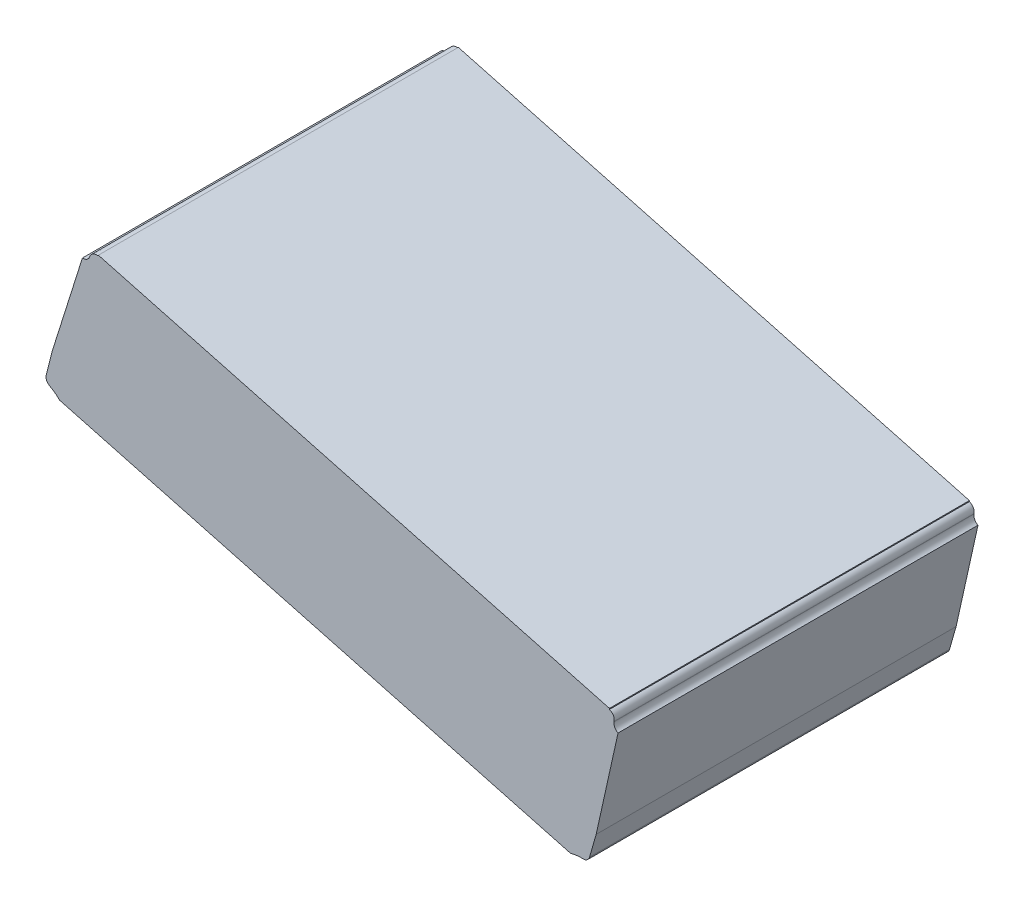
SolidWorks part; units mm, degrees
ref_plane "Płaszczyzna przednia" through (0, 0, 0) normal (0, 0, 1) x (1, 0, 0)
ref_plane "Płaszczyzna górna" through (0, 0, 0) normal (0, 1, 0) x (1, 0, 0)
ref_plane "Płaszczyzna prawa" through (0, 0, 0) normal (1, 0, 0) x (0, 0, -1)
sketch "Sketch1" plane through (0, 0, 0) normal (0, 0, 1) x (-1, 0, 0)
  line L16 (67.9733, -37.6562) -> (68.0043, -37.571)
  line L17 (70.0307, -36.2604) -> (78.48, -9.4628)
  line L18 (78.48, -9.4628) -> (80.0914, -3)
  line L19 (76.3919, 1.1164) -> (-65.5992, 39.1628)
  line L20 (-70.8611, 37.4476) -> (-72.6971, 31.0449)
  line L21 (-72.6971, 31.0449) -> (-78.7786, 3.6129)
  line L22 (-77.6789, 1.4647) -> (-77.6947, 1.3754)
  line L23 (-76.3919, -1.1164) -> (65.5992, -39.1628)
  arc A20 (65.5992, -39.1628) -> (65.7321, -38.9392) centre (0, 0) ccw
  arc A21 (65.7321, -38.9392) -> (67.9733, -37.6562) centre (66.0939, -36.9721) ccw
  arc A22 (70.0307, -36.2604) -> (68.0043, -37.571) centre (69.8837, -38.255) ccw
  arc A23 (80.0914, -3) -> (79.1595, -0.9594) centre (78.3448, -2.5645) ccw
  arc A24 (76.3919, 1.1164) -> (79.1595, -0.9594) centre (83.6855, 7.9577) ccw
  arc A25 (-69.0338, 38.7489) -> (-65.5992, 39.1628) centre (-68.4949, 48.7343) ccw
  arc A26 (-69.0338, 38.7489) -> (-70.8611, 37.4476) centre (-69.1309, 36.9515) ccw
  arc A27 (-77.6789, 1.4647) -> (-78.7786, 3.6129) centre (-79.6486, 1.812) ccw
  arc A28 (-77.6947, 1.3754) -> (-76.3953, -0.8562) centre (-75.7251, 1.0281) ccw
  arc A29 (-76.3953, -0.8562) -> (-76.3919, -1.1164) centre (0, 0) ccw
extrude "Boss-Extrude1" add sketch "Sketch1" along normal blind 100 contours L23 A20 A21 L16 A22 L17 L18 A23 A24 L19 A25 A26 L20 L21 A27 L22 A28 A29
